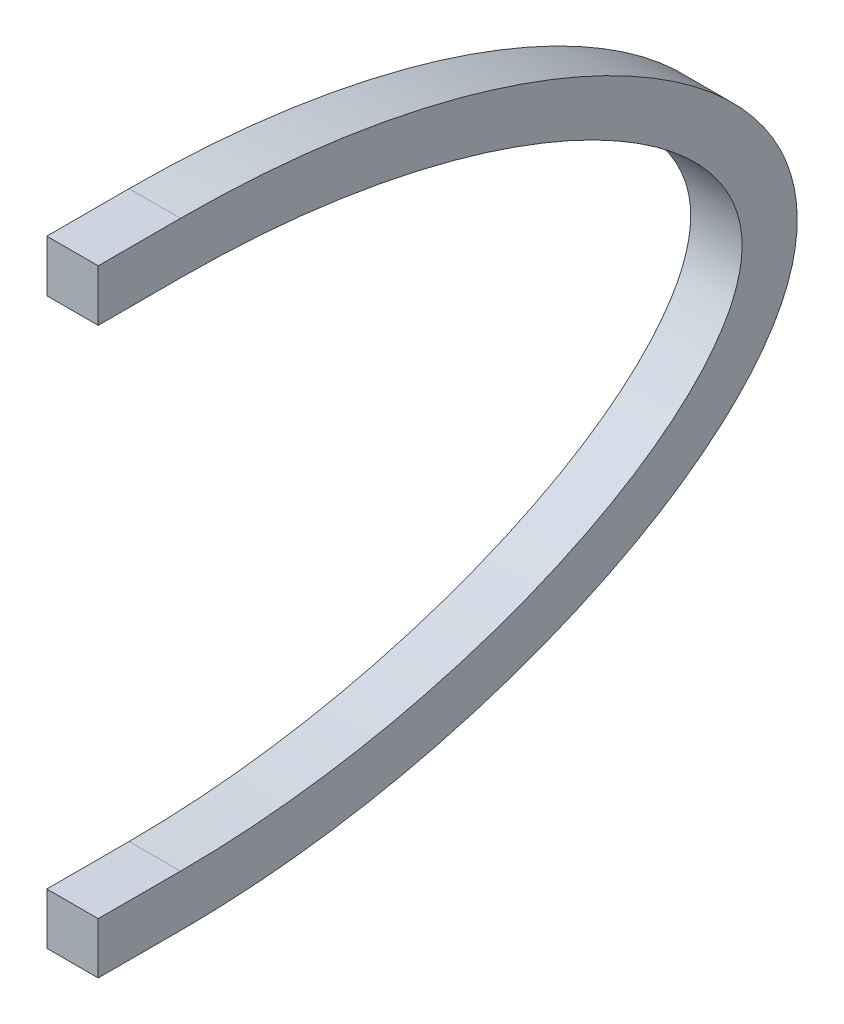
SolidWorks part; units mm, degrees
ref_plane "Front Plane" through (0, 0, 0) normal (0, 0, 1) x (1, 0, 0)
ref_plane "Top Plane" through (0, 0, 0) normal (0, 1, 0) x (1, 0, 0)
ref_plane "Right Plane" through (0, 0, 0) normal (1, 0, 0) x (0, 0, -1)
sketch "Sketch1" plane through (0, 0, 0) normal (1, 0, 0) x (0, 0, -1)
  line L0 (0, 30.0098) -> (-8, 30.0098)
  line L2 (0, 30.0098) -> (0, 24.9901)
  line L3 (0, -24.9901) -> (0, -29.9902)
  line L4 (0, 24.9901) -> (0, -24.9901) construction
  line L5 (-8, 30.0098) -> (-8, 24.9901)
  line L6 (-8, 24.9901) -> (0, 24.9901)
  line L7 (0, -24.9901) -> (-8, -24.9901)
  line L8 (-8, -24.9901) -> (-8, -29.9902)
  line L9 (-8, -29.9902) -> (0, -29.9902)
  line L10 (0, 0) -> (60, 0) construction
  spline S0 degree 3 poles (0, 24.9901) (30.1407, 24.9901) (80.2141, 0) (27.9634, -24.9901) (0, -24.9901) knots 0 0 0 0 0.5 1 1 1 1
  spline S2 degree 3 poles (0, 30.0098) (29.7778, 30.0098) (59.9447, 15.7249) (60.5708, -15.4539) (27.8424, -29.9902) (0, -29.9902) knots 0 0 0 0 0.453232 0.553232 1 1 1 1
  spline S6 degree 3 poles (0, -24.9901) (0.0014, -24.9901) (0.0069, -24.9901) (0.0125, -24.9901) (0.0166, -24.9902) knots 0.999914 0.999914 0.999914 0.999914 0.999936 1 1 1 1 construction
  point P20 (0, 0)
  dimension "D1" = 8
  dimension "D2" = 5.3669
  dimension "D5" = 60
  dimension "D6" = 60
extrude "Boss-Extrude1" add sketch "Sketch1" along normal mid plane 5 contours L2 S2 | L9 L8 L7 L3 | L6 L5 L0 L2
